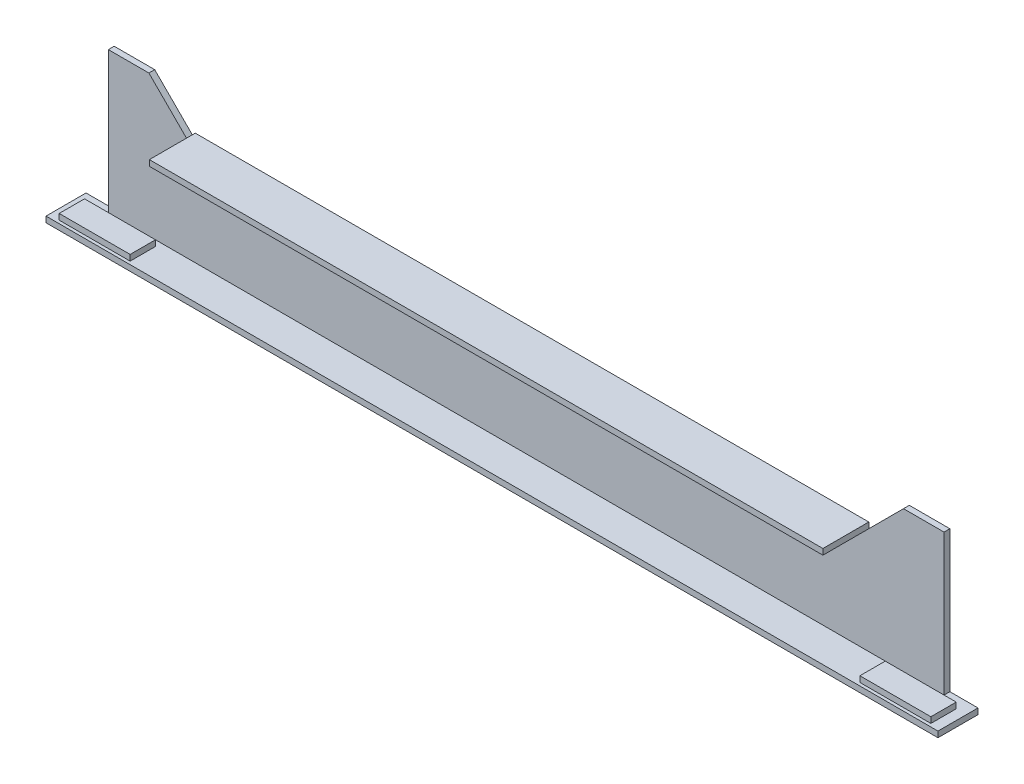
SolidWorks part; units mm, degrees
ref_plane "前视" through (0, 0, 0) normal (0, 0, 1) x (1, 0, 0)
ref_plane "上视" through (0, 0, 0) normal (0, 1, 0) x (1, 0, 0)
ref_plane "右视" through (0, 0, 0) normal (1, 0, 0) x (0, 0, -1)
sketch "草图1" plane through (0, 0, 0) normal (0, 0, 1) x (1, 0, 0)
  line L0 (0, 0) -> (1088.881, 0) construction
  line L1 (1088.881, 0) -> (-981.9373, 0) construction
  line L2 (0, 0) -> (0, 345.1364) construction
  line L3 (0, 345.1364) -> (0, -374.3029) construction
  line L4 (-744.5, 139.25) -> (-664.5, 59.25)
  line L5 (-824.5, 139.25) -> (-744.5, 139.25)
  line L6 (-824.5, 139.25) -> (-824.5, -139.25)
  line L7 (-824.5, -139.25) -> (824.5, -139.25)
  line L8 (824.5, 139.25) -> (824.5, -139.25)
  line L9 (-664.5, 59.25) -> (664.5, 59.25)
  line L10 (744.5, 139.25) -> (664.5, 59.25)
  line L11 (744.5, 139.25) -> (824.5, 139.25)
  line L12 (-784.5, 294.6321) -> (-784.5, -374.3029) construction
  circle A0 centre (-784.5, 99.25) radius 13
  circle A1 centre (-784.5, 19.25) radius 13
  circle A2 centre (-784.5, -60.75) radius 13
  circle A3 centre (784.5, -60.75) radius 13
  circle A4 centre (784.5, 19.25) radius 13
  circle A5 centre (784.5, 99.25) radius 13
  point P15 (0, 59.25)
  point P17 (0, 59.25)
  dimension "D8" = 26
  dimension "D1" = 1649
  dimension "D2" = 278.5
  dimension "D3" = 80
  dimension "D4" = 80
  dimension "D5" = 80
  dimension "D6" = 40
  dimension "D7" = 40
  dimension "D9" = 80
  dimension "D10" = 80
extrude "基体-拉伸" add sketch "草图1" along normal blind 11.5
sketch "草图2" plane through (0, 0, 11.5) normal (0, 0, 1) x (1, 0, 0)
  line L0 (0, 0) -> (0, 521.0174) construction
  line L1 (-664.5, 59.25) -> (664.5, 59.25)
  line L2 (-664.5, 59.25) -> (-664.5, 70.75)
  line L3 (-664.5, 70.75) -> (664.5, 70.75)
  line L4 (664.5, 59.25) -> (664.5, 70.75)
  dimension "D1" = 11.5
extrude "凸台-拉伸7" add sketch "草图2" along normal blind 79 and the other way through all
sketch "草图3" plane through (0, 0, 11.5) normal (0, 0, 1) x (1, 0, 0)
  line L0 (0, 567.7533) -> (0, -567.7533) construction
  line L2 (880, -139.25) -> (-880, -139.25)
  line L3 (880, -139.25) -> (880, -150.75)
  line L4 (880, -150.75) -> (-880, -150.75)
  line L5 (-880, -139.25) -> (-880, -150.75)
  line L6 (-824.5, -139.25) -> (824.5, -139.25) construction
  dimension "D1" = 1760
  dimension "D2" = 11.5
extrude "凸台-拉伸9" add sketch "草图3" along normal blind 67.5 and the other way blind 11.5
sketch "草图4" plane through (0, -139.25, 0) normal (0, 1, 0) x (-1, 0, 0)
  line L0 (-937.8047, 48) -> (1011.0707, 48) construction
  line L2 (-880, 0) -> (-824.5, 0) construction
  line L4 (0, 392.3282) -> (0, -456.8038) construction
  line L5 (-720, 23) -> (-860, 23)
  line L6 (-720, 23) -> (-720, 73)
  line L7 (-720, 73) -> (-860, 73)
  line L8 (-860, 23) -> (-860, 73)
  line L10 (720, 73) -> (860, 73)
  line L11 (860, 23) -> (860, 73)
  line L12 (720, 23) -> (860, 23)
  line L13 (720, 23) -> (720, 73)
  dimension "D1" = 48
  dimension "D2" = 50
  dimension "D3" = 720
  dimension "D4" = 140
extrude "凸台-拉伸10" add sketch "草图4" along normal blind 11.5
sketch "草图6" plane through (0, -150.75, 0) normal (0, -1, 0) x (1, 0, 0)
  line L0 (0, -191.3381) -> (0, 599.3241) construction
  line L1 (-998.2492, 48) -> (946.3524, 48) construction
  line L2 (-760, -191.3381) -> (-760, 330.6821) construction
  line L3 (-840, 330.6821) -> (-840, -191.3381) construction
  line L4 (-880, 0) -> (880, 0) construction
  circle A0 centre (-840, 48) radius 13
  circle A1 centre (-760, 48) radius 13
  circle A2 centre (760, 48) radius 13
  circle A3 centre (840, 48) radius 13
  dimension "D4" = 26
  dimension "D1" = 48
  dimension "D2" = 760
  dimension "D3" = 80
extrude "切除-拉伸1" cut sketch "草图6" against normal through all
sketch "草图7" plane through (0, 0, 11.5) normal (0, 0, 1) x (1, 0, 0)
  line L0 (-824.5, 139.25) -> (-744.5, 139.25)
  line L1 (-744.5, 139.25) -> (-664.5, 59.25)
  line L2 (-664.5, 59.25) -> (664.5, 59.25)
  line L3 (664.5, 59.25) -> (744.5, 139.25)
  line L4 (744.5, 139.25) -> (824.5, 139.25)
  line L5 (824.5, 139.25) -> (824.5, -139.25)
  line L6 (720, -139.25) -> (860, -139.25) construction
  line L7 (880, -139.25) -> (-880, -139.25) construction
  line L8 (824.5, -139.25) -> (-824.5, -139.25)
  line L9 (-860, -139.25) -> (-720, -139.25) construction
  line L10 (-824.5, -139.25) -> (824.5, -139.25) construction
  line L11 (-824.5, -139.25) -> (-824.5, 139.25)
extrude "凸台-拉伸11" add sketch "草图7" against normal blind 11.5
sketch "草图8" plane through (0, -127.75, 0) normal (0, 1, 0) x (1, 0, 0)
  line L1 (-860, -23) -> (-720, -23)
  line L2 (-860, -23) -> (-860, -73)
  line L3 (-860, -73) -> (-720, -73)
  line L4 (-720, -23) -> (-720, -73)
  line L5 (720, -23) -> (860, -23)
  line L6 (720, -23) -> (720, -73)
  line L7 (720, -73) -> (860, -73)
  line L8 (860, -23) -> (860, -73)
extrude "凸台-拉伸12" add sketch "草图8" against normal blind 23
